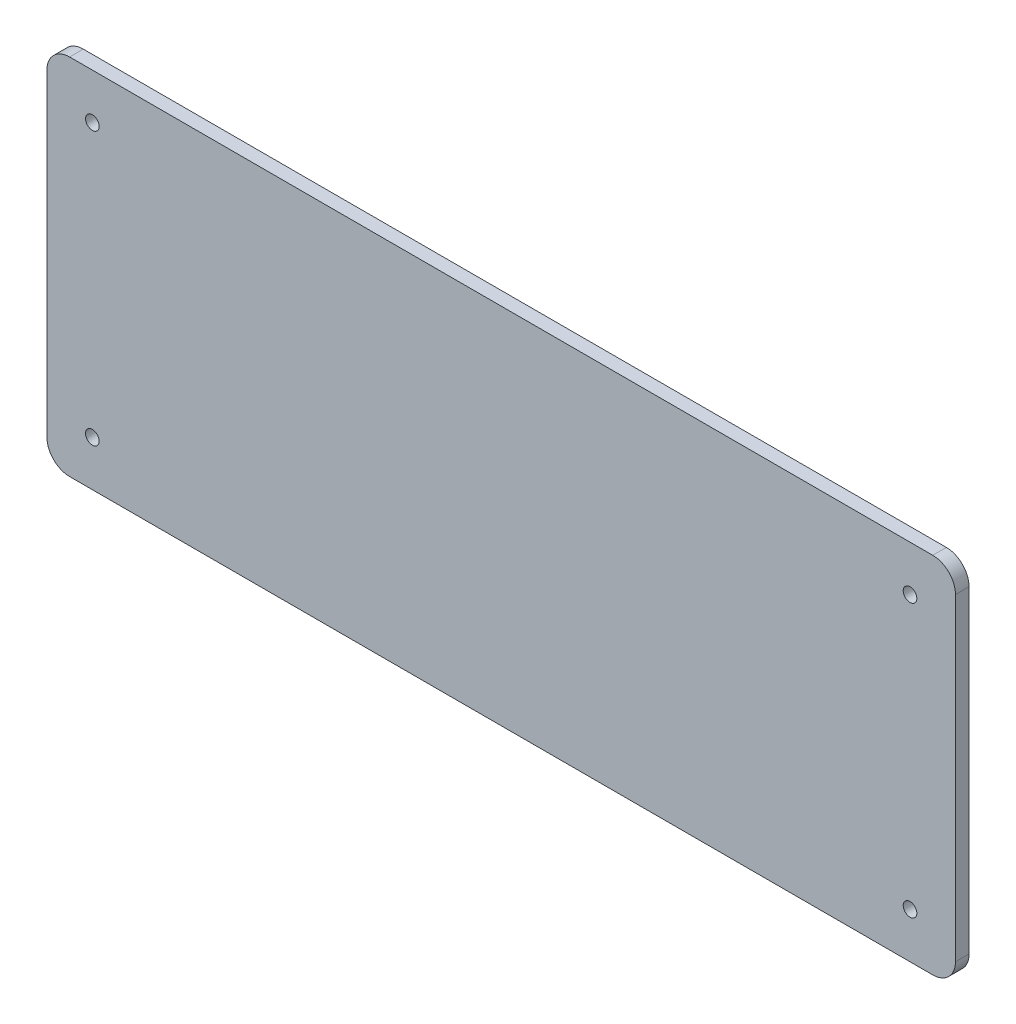
SolidWorks part; units mm, degrees
ref_plane "Plano frontal" through (0, 0, 0) normal (0, 0, 1) x (1, 0, 0)
ref_plane "Plano superior" through (0, 0, 0) normal (0, 1, 0) x (1, 0, 0)
ref_plane "Plano direito" through (0, 0, 0) normal (1, 0, 0) x (0, 0, -1)
sketch "Esboço1" plane through (0, 0, 0) normal (0, 0, 1) x (1, 0, 0)
  line L1 (95, -40) -> (-95, -40)
  line L2 (100, -35) -> (100, 35)
  line L3 (95, 40) -> (-95, 40)
  line L4 (-100, -35) -> (-100, 35)
  line L5 (100, -40) -> (-100, 40) construction
  line L6 (100, 40) -> (-100, -40) construction
  circle A0 centre (-90, 30) radius 1.5
  circle A1 centre (90, 30) radius 1.5
  circle A2 centre (90, -30) radius 1.5
  circle A3 centre (-90, -30) radius 1.5
  arc A4 (100, 35) -> (95, 40) centre (95, 35) ccw
  arc A5 (95, -40) -> (100, -35) centre (95, -35) ccw
  arc A6 (-95, -40) -> (-100, -35) centre (-95, -35) cw
  arc A7 (-95, 40) -> (-100, 35) centre (-95, 35) ccw
  point P0 (0, 0)
  dimension "D5" = 3
  dimension "D4" = 10
  dimension "D8" = 10
  dimension "D9" = 10
  dimension "D10" = 90
  dimension "D11" = 5
  dimension "D1" = 80
  dimension "D2" = 200
  dimension "D3" = 10
  dimension "D6" = 2
  dimension "D7" = 2
extrude "Ressalto-extrusão1" add sketch "Esboço1" along normal blind 3
